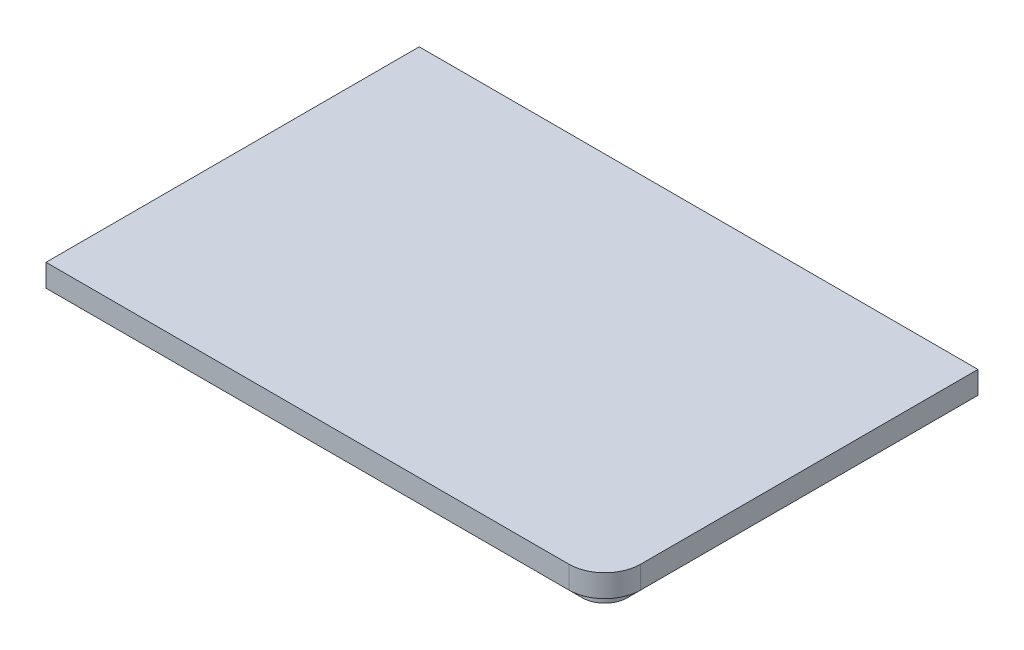
SolidWorks part; units mm, degrees
ref_plane "Alzado" through (0, 0, 0) normal (0, 0, 1) x (1, 0, 0)
ref_plane "Planta" through (0, 0, 0) normal (0, 1, 0) x (1, 0, 0)
ref_plane "Vista lateral" through (0, 0, 0) normal (1, 0, 0) x (0, 0, -1)
sketch "Croquis1" plane through (0, 0, 0) normal (0, 1, 0) x (1, 0, 0)
  line L1 (-62.245, -41.575) -> (54.245, -41.575)
  line L2 (-62.245, -41.575) -> (-62.245, 41.575)
  line L3 (-62.245, 41.575) -> (62.245, 41.575)
  line L4 (62.245, -33.575) -> (62.245, 41.575)
  line L5 (-62.245, -41.575) -> (62.245, 41.575) construction
  line L6 (-62.245, 41.575) -> (62.245, -41.575) construction
  arc A0 (54.245, -41.575) -> (62.245, -33.575) centre (54.245, -33.575) ccw
  point P0 (0, 0)
  dimension "D3" = 8
  dimension "D1" = 124.49
  dimension "D2" = 83.15
extrude "Saliente-Extruir1" add sketch "Croquis1" along normal blind 5
sketch "Croquis2" plane through (0, 0, 0) normal (0, 1, 0) x (1, 0, 0)
  line L0 (52.245, -31.575) -> (52.245, 31.575)
  line L1 (21.4, 31.575) -> (-62.245, 31.575)
  line L3 (-62.245, -31.575) -> (52.245, -31.575)
  line L4 (62.245, -33.575) -> (62.245, 41.575)
  line L5 (62.245, 41.575) -> (-62.245, 41.575)
  line L6 (-62.245, 41.575) -> (-62.245, -41.575)
  line L7 (-62.245, -41.575) -> (54.245, -41.575)
  line L10 (-62.245, 31.575) -> (-62.245, 36.575)
  line L12 (52.245, 31.575) -> (-52.245, 31.575) construction
  line L13 (-52.245, -31.575) -> (52.245, -31.575) construction
  line L14 (-52.245, 31.575) -> (-52.245, -31.575) construction
  line L15 (-62.245, 41.575) -> (-62.245, -41.575) construction
  line L16 (62.245, 41.575) -> (-62.245, 41.575) construction
  line L17 (62.245, -33.575) -> (62.245, 41.575) construction
  line L18 (-62.245, -41.575) -> (54.245, -41.575) construction
  line L20 (-62.245, -36.575) -> (52.245, -36.575)
  line L21 (57.245, -31.575) -> (57.245, 36.575)
  line L22 (57.245, 36.575) -> (-62.245, 36.575)
  line L23 (57.245, 36.575) -> (-67.245, 36.575) construction
  line L24 (-67.245, -36.575) -> (52.245, -36.575) construction
  line L25 (-62.245, -36.575) -> (-62.245, -31.575)
  line L26 (-62.245, 31.575) -> (-62.245, -31.575) construction
  line L27 (-67.245, 36.575) -> (-67.245, -36.575) construction
  line L28 (52.245, 31.575) -> (-62.245, 31.575) construction
  line L29 (52.245, -31.575) -> (52.245, 31.575) construction
  line L30 (21.4, 31.575) -> (52.245, 31.575)
  arc A0 (52.245, -31.575) -> (52.245, -31.575) centre (52.245, -31.575) ccw
  arc A1 (54.245, -41.575) -> (62.245, -33.575) centre (54.245, -33.575) ccw
  arc A3 (54.245, -41.575) -> (62.245, -33.575) centre (54.245, -33.575) ccw construction
  arc A4 (52.245, -36.575) -> (57.245, -31.575) centre (52.245, -31.575) ccw
  dimension "D3" = 5
  dimension "D2" = 73.15
  dimension "D1" = 0
extrude "Saliente-Extruir2" add sketch "Croquis2" against normal blind 5
